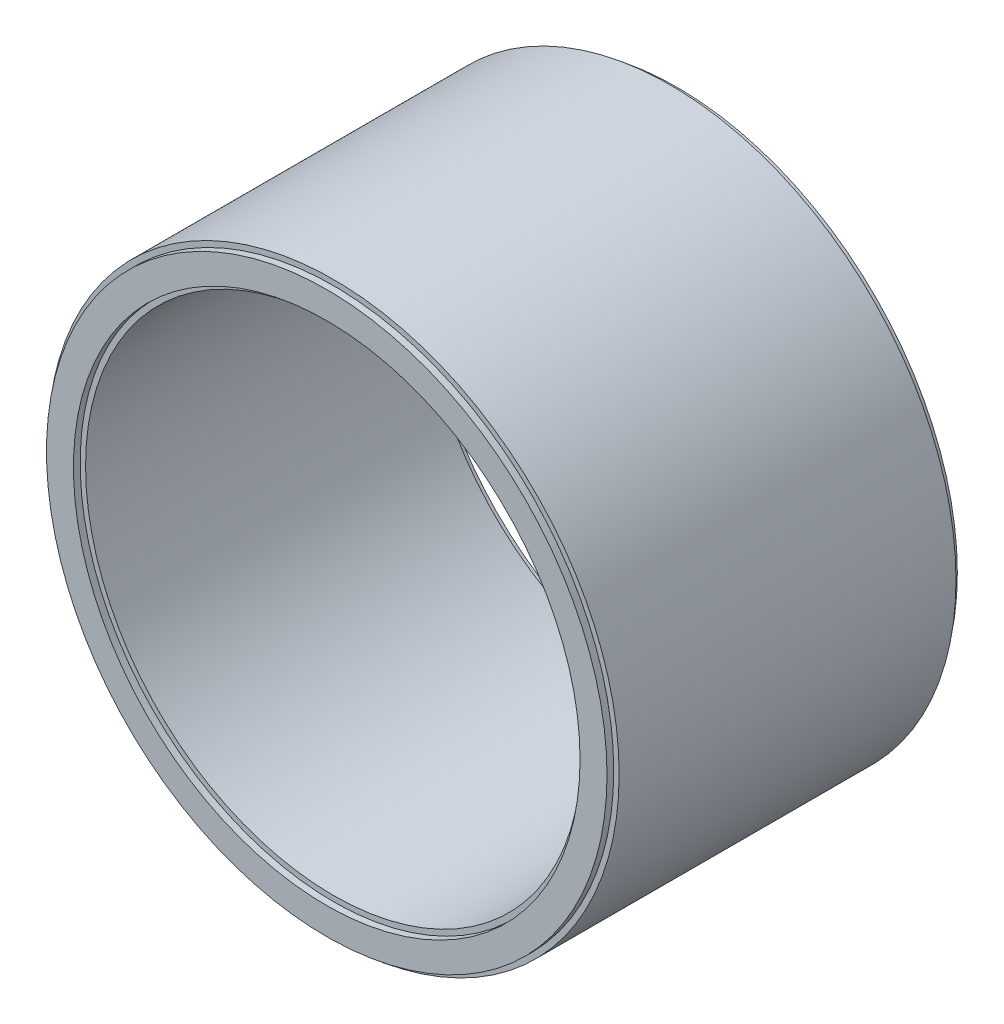
SolidWorks part; units mm, degrees
ref_plane "Plan de face" through (0, 0, 0) normal (0, 0, 1) x (1, 0, 0)
ref_plane "Plan de dessus" through (0, 0, 0) normal (0, 1, 0) x (1, 0, 0)
ref_plane "Plan de droite" through (0, 0, 0) normal (1, 0, 0) x (0, 0, -1)
sketch "Esquisse2" plane through (0, 0, 0) normal (1, 0, 0) x (0, 0, -1)
  line L12 (-6.5, 10.4) -> (-6.25, 10.4)
  line L13 (-6.25, 10.4) -> (-6.25, 10.6)
  line L14 (-6.25, 10.6) -> (6.25, 10.6)
  line L15 (6.25, 10.6) -> (6.25, 10.4)
  line L16 (6.25, 10.4) -> (6.5, 10.4)
  line L17 (6.5, 10.4) -> (6.5, 9.4)
  line L18 (6.5, 9.4) -> (6.25, 9.4)
  line L19 (6.25, 9.4) -> (6.25, 9.2)
  line L20 (6.25, 9.2) -> (-6.25, 9.2)
  line L21 (-6.25, 9.2) -> (-6.25, 9.4)
  line L22 (-6.25, 9.4) -> (-6.5, 9.4)
  line L23 (-6.5, 9.4) -> (-6.5, 10.4)
  line L24 (-6.8836, 0) -> (6.5, 0) construction
  point P17 (0, 9.2)
  dimension "D1" = 10.6
  dimension "D2" = 9.2
  dimension "D3" = 13
  dimension "D4" = 12.5
  dimension "D5" = 1
revolve "Révolution1" add sketch "Esquisse2" angle 360 about L24
